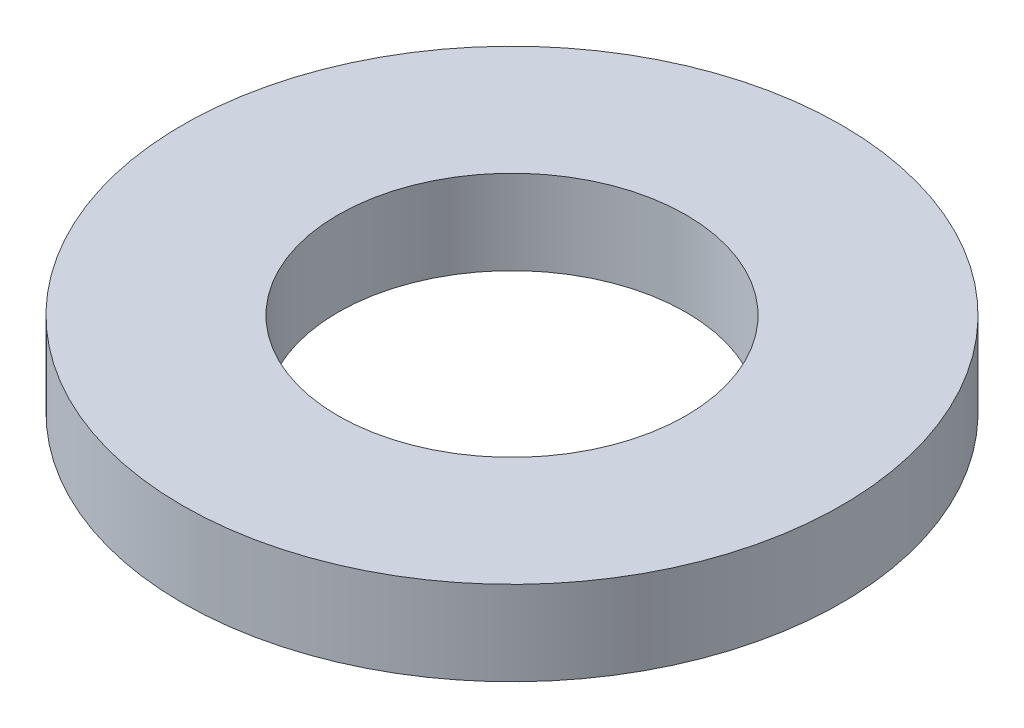
SolidWorks part; units mm, degrees
material "ASTM A36 Steel"
ref_plane "Front Plane" through (0, 0, 0) normal (0, 0, 1) x (1, 0, 0)
ref_plane "Top Plane" through (0, 0, 0) normal (0, 1, 0) x (1, 0, 0)
ref_plane "Right Plane" through (0, 0, 0) normal (1, 0, 0) x (0, 0, -1)
sketch "BodySke" plane through (0, 0, 0) normal (0, 0, -1) x (1, 0, 0)
  line L0 (0, 0) -> (0, 7.8986) construction
  line L2 (3.3, 1.6) -> (6.25, 1.6)
  line L3 (3.3, 1.6) -> (3.3, 0)
  line L4 (3.3, 0) -> (6.25, 0)
  line L5 (6.25, 1.6) -> (6.25, 0)
  dimension "Inner_dia" = 6.6
  dimension "Outer_dia" = 12.5
  dimension "Thickness" = 1.6
revolve "BaseBody" add sketch "BodySke" angle 360 about L0
